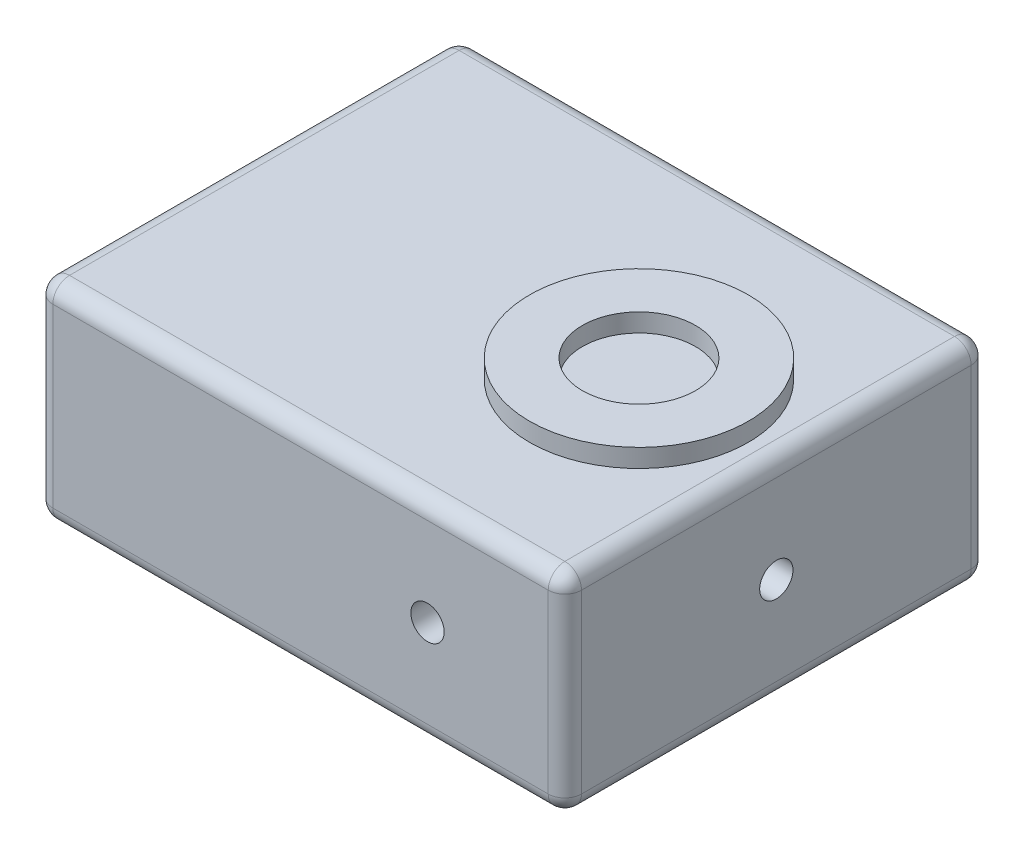
SolidWorks part; units mm, degrees
material "Stainless Steel (ferritic)"
ref_plane "Front Plane" through (0, 0, 0) normal (0, 0, 1) x (1, 0, 0)
ref_plane "Top Plane" through (0, 0, 0) normal (0, 1, 0) x (1, 0, 0)
ref_plane "Right Plane" through (0, 0, 0) normal (1, 0, 0) x (0, 0, -1)
sketch "Sketch1" plane through (0, 0, 0) normal (0, 1, 0) x (1, 0, 0)
  line L1 (-31.75, -25.4) -> (31.75, -25.4)
  line L2 (-31.75, -25.4) -> (-31.75, 25.4)
  line L3 (-31.75, 25.4) -> (31.75, 25.4)
  line L4 (31.75, -25.4) -> (31.75, 25.4)
  line L5 (-31.75, -25.4) -> (31.75, 25.4) construction
  line L6 (-31.75, 25.4) -> (31.75, -25.4) construction
  point P0 (0, 0)
  dimension "D1" = 63.5
  dimension "D2" = 50.8
extrude "Boss-Extrude1" add sketch "Sketch1" along normal blind 25.2
sketch "Sketch2" plane through (0, 25.2, 0) normal (0, 1, 0) x (1, 0, 0)
  line L0 (-31.75, -25.4) -> (31.75, -25.4) construction
  line L2 (31.75, -25.4) -> (31.75, 25.4) construction
  circle A0 centre (15.25, 0) radius 13.1445
  circle A1 centre (15.25, 0) radius 6.7945
  dimension "D1" = 26.289
  dimension "D2" = 13.589
  dimension "D3" = 25.4
  dimension "D4" = 16.5
extrude "Boss-Extrude2" add sketch "Sketch2" along normal blind 2.2
sketch "Sketch3" plane through (0, 0, 25.4) normal (0, 0, 1) x (1, 0, 0)
  line L0 (31.75, 25.2) -> (31.75, 0) construction
  circle A0 centre (15.25, 12.6) radius 2
  point P4 (31.75, 12.6)
  dimension "D1" = 4
  dimension "D2" = 16.5
extrude "Cut-Extrude1" cut sketch "Sketch3" against normal blind 5.5
sketch "Sketch4" plane through (31.75, 0, 0) normal (1, 0, 0) x (0, 0, -1)
  line L0 (-25.4, 25.2) -> (25.4, 25.2) construction
  line L1 (-25.4, 25.2) -> (-25.4, 0) construction
  circle A0 centre (0, 12.6) radius 2
  point P5 (0, 25.2)
  point P8 (-25.4, 12.6)
  dimension "D1" = 4
extrude "Cut-Extrude2" cut sketch "Sketch4" against normal blind 5.5
sketch "Sketch5" plane through (0, 0, -25.4) normal (0, 0, -1) x (-1, 0, 0)
  line L0 (-31.75, 25.2) -> (-31.75, 0) construction
  circle A0 centre (-15.25, 12.6) radius 2
  point P4 (-31.75, 12.6)
  dimension "D1" = 4
  dimension "D2" = 16.5
extrude "Cut-Extrude3" cut sketch "Sketch5" against normal blind 5.5
fillet "Fillet1" radius 2 12 edges at (31.75, 0, 0) (0, 0, -25.4) (-31.75, 0, 0) (0, 0, 25.4) (0, 25.2, -25.4) (-31.75, 25.2, 0) (0, 25.2, 25.4) (31.75, 12.6, 25.4) (-31.75, 12.6, 25.4) (-31.75, 12.6, -25.4) (31.75, 12.6, -25.4) (31.75, 25.2, 0)
sketch "Sketch6" plane through (0, 0, -25.4) normal (0, 0, -1) x (-1, 0, 0)
  line L0 (31.75, 23.2) -> (31.75, 2) construction
  line L1 (7.25, 2.5) -> (25.25, 2.5)
  line L2 (7.25, 2.5) -> (7.25, 14.5)
  line L3 (7.25, 14.5) -> (25.25, 14.5)
  line L4 (25.25, 2.5) -> (25.25, 14.5)
  line L5 (7.25, 2.5) -> (25.25, 14.5) construction
  line L6 (7.25, 14.5) -> (25.25, 2.5) construction
  line L7 (29.75, 0) -> (-29.75, 0) construction
  point P0 (16.25, 8.5)
  dimension "D1" = 18
  dimension "D2" = 12
  dimension "D3" = 6.5
  dimension "D4" = 2.5
extrude "Boss-Extrude3" add sketch "Sketch6" along normal blind 1
